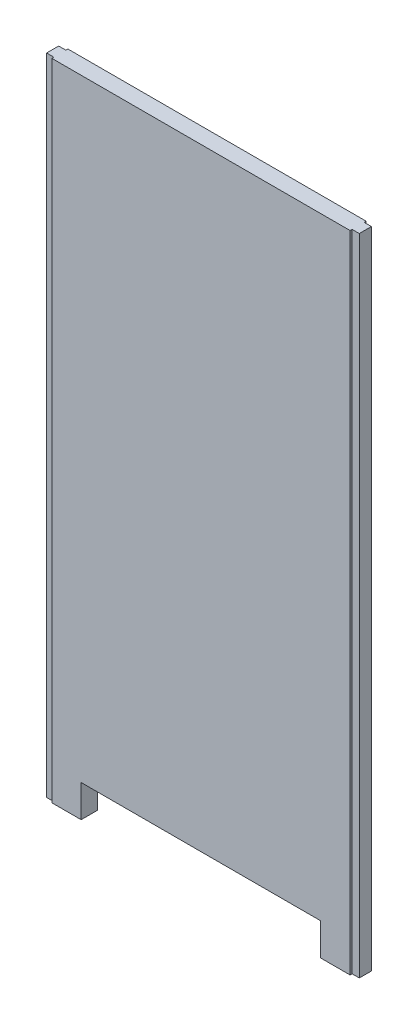
SolidWorks part; units mm, degrees
ref_plane "Front Plane" through (0, 0, 0) normal (0, 0, 1) x (1, 0, 0)
ref_plane "Top Plane" through (0, 0, 0) normal (0, 1, 0) x (1, 0, 0)
ref_plane "Right Plane" through (0, 0, 0) normal (1, 0, 0) x (0, 0, -1)
sketch "Sketch1" plane through (0, 0, 0) normal (0, 0, 1) x (1, 0, 0)
  line L1 (0, 0) -> (37, 0)
  line L2 (0, 0) -> (0, 80)
  line L3 (0, 80) -> (37, 80)
  line L4 (37, 0) -> (37, 80)
  dimension "D1" = 80
  dimension "D2" = 37
extrude "Boss-Extrude1" add sketch "Sketch1" along normal blind 2
sketch "Sketch2" plane through (0, 80, 0) normal (0, 1, 0) x (1, 0, 0)
  line L0 (0, -2) -> (0, 0) construction
  line L1 (37.9, -1) -> (37, -1) construction
  line L3 (37.9, -0.25) -> (37, -0.25)
  line L9 (18.5, 0) -> (18.5, -2) construction
  line L10 (37, 0) -> (0, 0) construction
  line L11 (37, -2) -> (0, -2) construction
  line L16 (37, -1.75) -> (37, -0.25)
  line L17 (37.9, -1.75) -> (37.9, -0.25)
  line L18 (-0.9, -1.75) -> (0, -1.75)
  line L19 (-0.9, -1.75) -> (-0.9, -0.25)
  line L20 (-0.9, -1) -> (0, -1) construction
  line L21 (0, -1.75) -> (0, -0.25)
  line L22 (-0.9, -0.25) -> (0, -0.25)
  line L23 (37.9, -1.75) -> (37, -1.75)
  dimension "D1" = 0.9
  dimension "D2" = 1.5
extrude "Boss-Extrude2" add sketch "Sketch2" against normal up to surface (80 mm away) up to face at (18.5, 0, 1)
sketch "Sketch3" plane through (0, 0, 2) normal (0, 0, 1) x (1, 0, 0)
  line L0 (0, 0) -> (18.5, 0) construction
  line L1 (0, 0) -> (37, 0) construction
  line L2 (18.5, 0) -> (18.5, 4) construction
  line L3 (3.6365, 4) -> (33.3635, 4)
  line L4 (33.3635, 4) -> (33.3635, 0)
  line L5 (3.6365, 4) -> (3.6365, 0)
  line L6 (3.6365, 0) -> (33.3635, 0)
  dimension "D1" = 4
extrude "Cut-Extrude1" cut sketch "Sketch3" against normal up to surface (2 mm away) contours L3 L4 L6 L5 up to face at (18.5, 40, 0)
